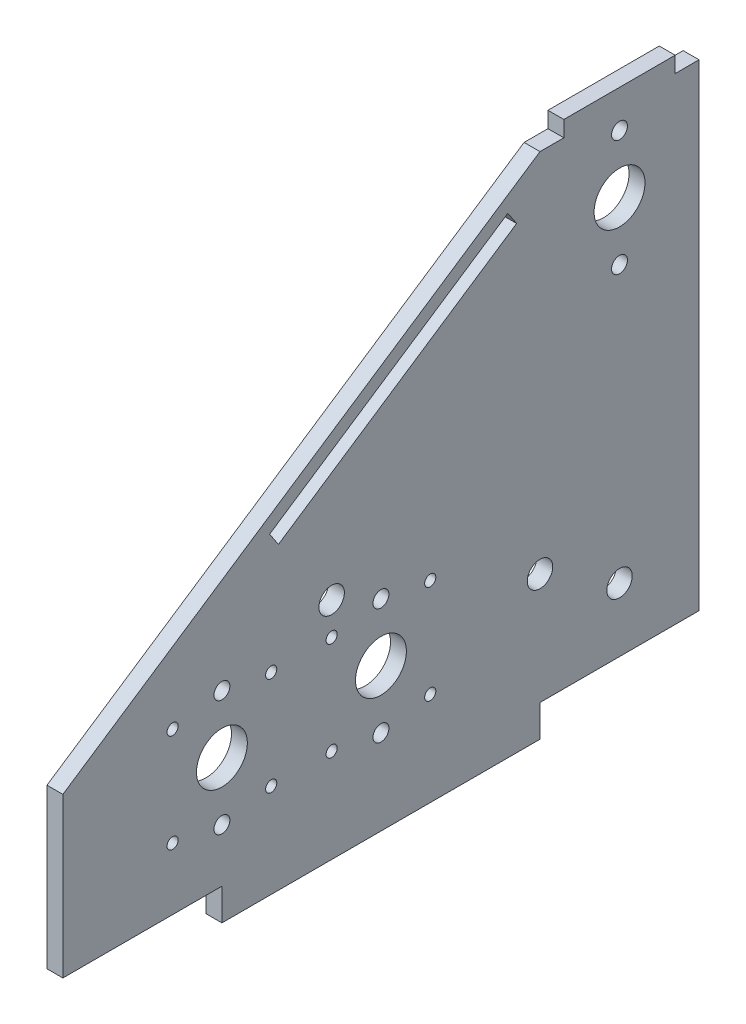
SolidWorks part; units mm, degrees
ref_plane "Alzado" through (0, 0, 0) normal (0, 0, 1) x (1, 0, 0)
ref_plane "Planta" through (0, 0, 0) normal (0, 1, 0) x (1, 0, 0)
ref_plane "Vista lateral" through (0, 0, 0) normal (1, 0, 0) x (0, 0, -1)
sketch "Croquis1" plane through (0, 0, 0) normal (1, 0, 0) x (0, 0, -1)
  line L0 (150, 150) -> (0, 50)
  line L1 (0, 0) -> (50, 0)
  line L2 (0, 0) -> (0, 50)
  line L3 (150, 150) -> (157.5, 150)
  line L4 (200, 0) -> (200, 150)
  line L5 (200, 75) -> (37.5, 75) construction
  line L6 (175, 155) -> (175, 0) construction
  line L7 (100, 116.6667) -> (100, -10) construction
  line L8 (84.5, 106.3333) -> (84.5, -10) construction
  line L9 (50, 0) -> (50, -10)
  line L10 (50, -10) -> (150, -10)
  line L11 (150, 0) -> (150, -10)
  line L12 (154, 35) -> (0, 35) construction
  line L13 (192.5, 150) -> (200, 150)
  line L14 (150, 0) -> (200, 0)
  line L15 (65, 88.3333) -> (139.8845, 138.2564)
  line L16 (157.5, 150) -> (157.5, 155)
  line L17 (157.5, 155) -> (192.5, 155)
  line L18 (192.5, 150) -> (192.5, 155)
  line L19 (139.8845, 138.2564) -> (142.658, 134.0961)
  line L20 (142.658, 134.0961) -> (67.7735, 84.1731)
  line L21 (67.7735, 84.1731) -> (65, 88.3333)
  line L22 (5, 53.3333) -> (5, 0) construction
  line L23 (65, 88.3333) -> (5, 48.3333) construction
  circle A0 centre (175, 125) radius 8
  circle A1 centre (175, 20) radius 4
  circle A2 centre (150, 35) radius 4
  circle A3 centre (175, 143.25) radius 2.5
  circle A4 centre (175, 106.75) radius 2.5
  circle A5 centre (100, 35) radius 8
  circle A6 centre (84.5, 60.6856) radius 4
  circle A7 centre (100, 53.25) radius 2.5
  circle A8 centre (100, 16.75) radius 2.5
  circle A9 centre (84.5, 50.5) radius 1.75
  circle A10 centre (115.5, 50.5) radius 1.75
  circle A11 centre (115.5, 19.5) radius 1.75
  circle A12 centre (84.5, 19.5) radius 1.75
  circle A13 centre (50, 35) radius 8
  circle A14 centre (50, 53.25) radius 2.5
  circle A15 centre (50, 16.75) radius 2.5
  circle A16 centre (34.5, 50.5) radius 1.75
  circle A17 centre (65.5, 50.5) radius 1.75
  circle A18 centre (65.5, 19.5) radius 1.75
  circle A19 centre (34.5, 19.5) radius 1.75
  dimension "D6" = 16
  dimension "D10" = 8
  dimension "D12" = 8
  dimension "D15" = 5
  dimension "D16" = 5
  dimension "D20" = 45
  dimension "D22" = 2
  dimension "D23" = 18.25
  dimension "D24" = 5
  dimension "D27" = 3.5
  dimension "D21" = 8
  dimension "D1" = 150
  dimension "D2" = 200
  dimension "D3" = 50
  dimension "D4" = 50
  dimension "D5" = 50
  dimension "D7" = 100
  dimension "D8" = 50
  dimension "D9" = 10
  dimension "D11" = 20
  dimension "D13" = 25
  dimension "D14" = 15
  dimension "D17" = 18.25
  dimension "D18" = 18.25
  dimension "D19" = 30
  dimension "D25" = 2
  dimension "D26" = 15.5
  dimension "D28" = 15.5
  dimension "D31" = 35
  dimension "D32" = 5
  dimension "D33" = 90
  dimension "D34" = 15
  dimension "D35" = 5
  dimension "D36" = 5
  dimension "D37" = 35
  dimension "D29" = 2
  dimension "D30" = 2
extrude "Saliente-Extruir1" add sketch "Croquis1" along normal blind 5
